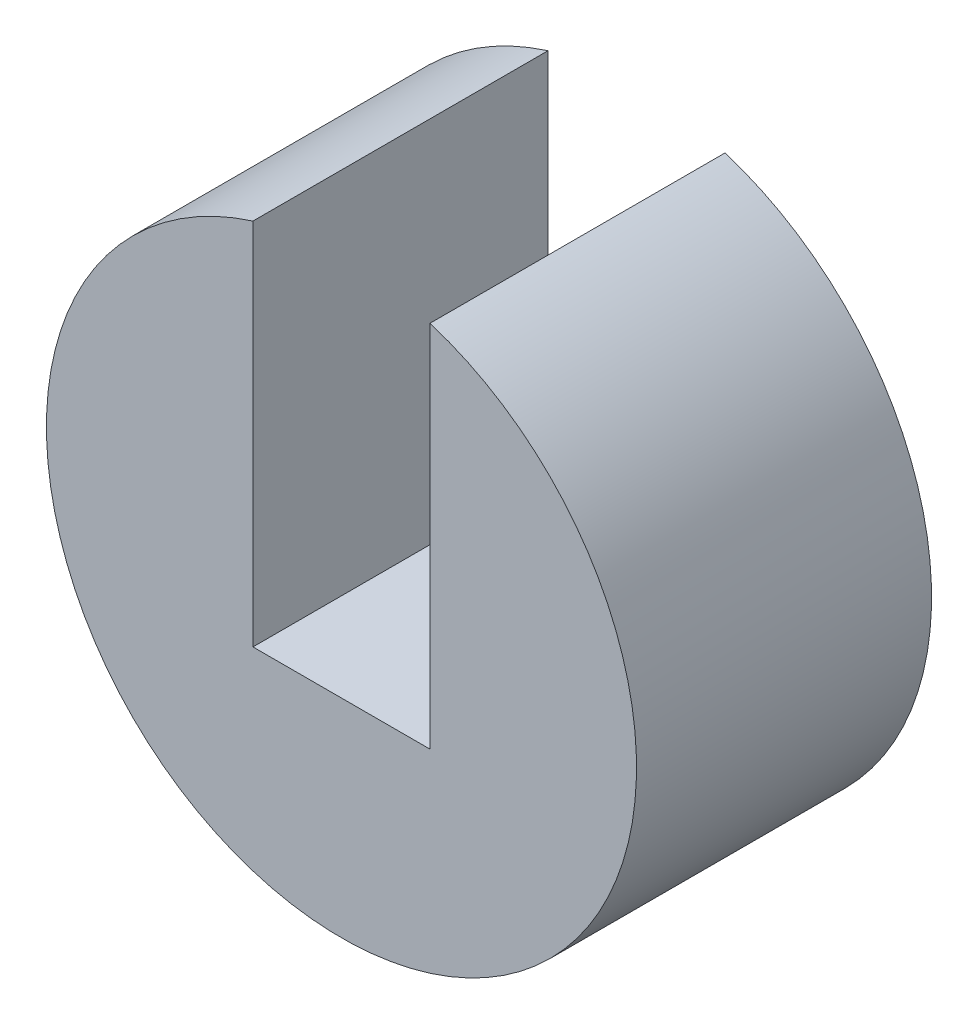
SolidWorks part; units mm, degrees
ref_plane "Front Plane" through (0, 0, 0) normal (0, 0, 1) x (1, 0, 0)
ref_plane "Top Plane" through (0, 0, 0) normal (0, 1, 0) x (1, 0, 0)
ref_plane "Right Plane" through (0, 0, 0) normal (1, 0, 0) x (0, 0, -1)
sketch "Sketch1" plane through (0, 0, 0) normal (0, 0, 1) x (1, 0, 0)
  line L1 (1.5, -3.125) -> (-1.5, -3.125)
  line L2 (1.5, -3.125) -> (1.5, 3.125)
  line L3 (1.5, 3.125) -> (-1.5, 3.125)
  line L4 (-1.5, -3.125) -> (-1.5, 3.125)
  line L5 (1.5, -3.125) -> (-1.5, 3.125) construction
  line L6 (1.5, 3.125) -> (-1.5, -3.125) construction
  circle A0 centre (0, -1.6447) radius 5
  point P0 (0, 0)
  dimension "D3" = 10
  dimension "D1" = 3
  dimension "D2" = 6.25
extrude "Boss-Extrude1" add sketch "Sketch1" along normal blind 5 contours L4 A0 L2 L1
